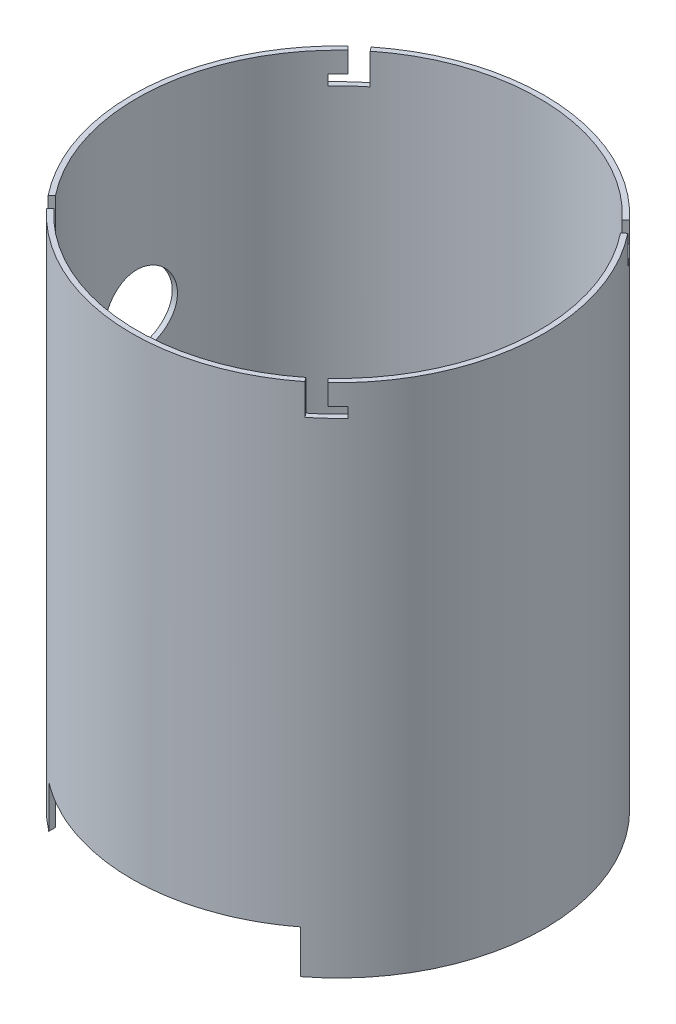
SolidWorks part; units mm, degrees
other "标注1"
sketch "草图11" plane through (200, -0.014, 200) normal (0.3513, -0.0928, 0.9316) x (0.927, -0.1054, -0.36)
ref_plane "前视基准面" through (0, 0, 0) normal (0, 0, 1) x (1, 0, 0)
ref_plane "上视基准面" through (0, 0, 0) normal (0, 1, 0) x (1, 0, 0)
ref_plane "右视基准面" through (0, 0, 0) normal (1, 0, 0) x (0, 0, -1)
ref_axis "旋转轴" through (0, -25.0147, 0) along (0, 1, 0)
sketch "草图1" plane through (0, 0, 0) normal (0, 1, 0) x (1, 0, 0)
  circle A0 centre (0, 0) radius 200
  circle A1 centre (0, 0) radius 195
extrude "主体" add sketch "草图1" along normal blind 500
sketch "草图8" plane through (0, 0, 280) normal (0, 0, 1) x (1, 0, 0)
  line L0 (65.2665, 41.8) -> (-65.2665, 41.8) construction
  line L1 (-122, 41.8) -> (122, 41.8)
  line L2 (-122, 41.8) -> (-122, 0)
  line L3 (-122, 0) -> (122, 0)
  line L4 (122, 41.8) -> (122, 0)
  line L5 (-122, 19.65) -> (-122, 60.35) construction
  line L6 (-213.4, 0) -> (213.4, 0) construction
  line L7 (122, 60.35) -> (122, 19.65) construction
extrude "操纵台开孔" cut sketch "草图8" against normal up to next from surface contours L2 L3 L4 L1
sketch "草图9" plane through (0, 0, 0) normal (1, 0, 0) x (0, 0, -1)
  line L0 (0, 220) -> (0, -220) construction
  line L2 (0, 180) -> (0, 224) construction
  line L3 (-158.4804, 0) -> (200, 0) construction
  circle A0 centre (0, 180) radius 36
  point P15 (0, 183.7)
  point P17 (0, 183.7)
  dimension "D1" = 180
  dimension "D2" = 44
extrude "投放口开孔" cut sketch "草图9" against normal through all
sketch "草图10" plane through (0, 0, 0) normal (1, 0, 0) x (0, 0, -1)
  line L0 (0, 220) -> (0, -220) construction
  line L4 (195, 500) -> (-195, 500) construction
  circle A0 centre (0, 320) radius 36
  dimension "D1" = 180
extrude "出球口开孔" cut sketch "草图10" against normal up to next
sketch "草图14" plane through (0, 0, 0) normal (-0.682, 0, 0.7314) x (0.7314, 0, 0.682)
  line L0 (-200, 470) -> (-199.5128, 470) construction
  line L1 (-200, 480) -> (-175.8573, 480)
  line L2 (-200, 480) -> (-200, 470)
  line L3 (-200, 470) -> (-175.8573, 470)
  line L4 (-175.8573, 480) -> (-175.8573, 470)
revolve "切除-旋转1" cut sketch "草图14" angle 8.5 about axis through (0, -25.0147, 0) along (0, 1, 0)
sketch "草图16" plane through (0, 480, 0) normal (0, -1, 0) x (1, 0, 0)
  line L0 (-124.5029, -156.5216) -> (-121.3904, -152.6086)
  line L1 (-136.3997, -146.2707) -> (-132.9897, -142.614)
  line L2 (-121.3904, -152.6086) -> (-124.5029, -156.5216) construction
  line L3 (-132.9897, -142.614) -> (-136.3997, -146.2707) construction
  arc A0 (-132.9897, -142.614) -> (-121.3904, -152.6086) centre (0, 0) ccw
  arc A1 (-136.3997, -146.2707) -> (-124.5029, -156.5216) centre (0, 0) ccw
  arc A3 (-142.614, -132.9897) -> (-121.3904, -152.6086) centre (0, 0) ccw construction
  arc A4 (-146.2707, -136.3997) -> (-124.5029, -156.5216) centre (0, 0) ccw construction
extrude "切除-拉伸1" cut sketch "草图16" against normal up to next
pattern_circular "阵列(圆周)1" count 4 over 360 about axis through (0, -25.0147, 0) along (0, 1, 0) of "切除-旋转1", "切除-拉伸1"
equation "\"顶盖解锁角度\"=8.5"
equation "\"D1@切除-旋转1\"=\"顶盖解锁角度\""
